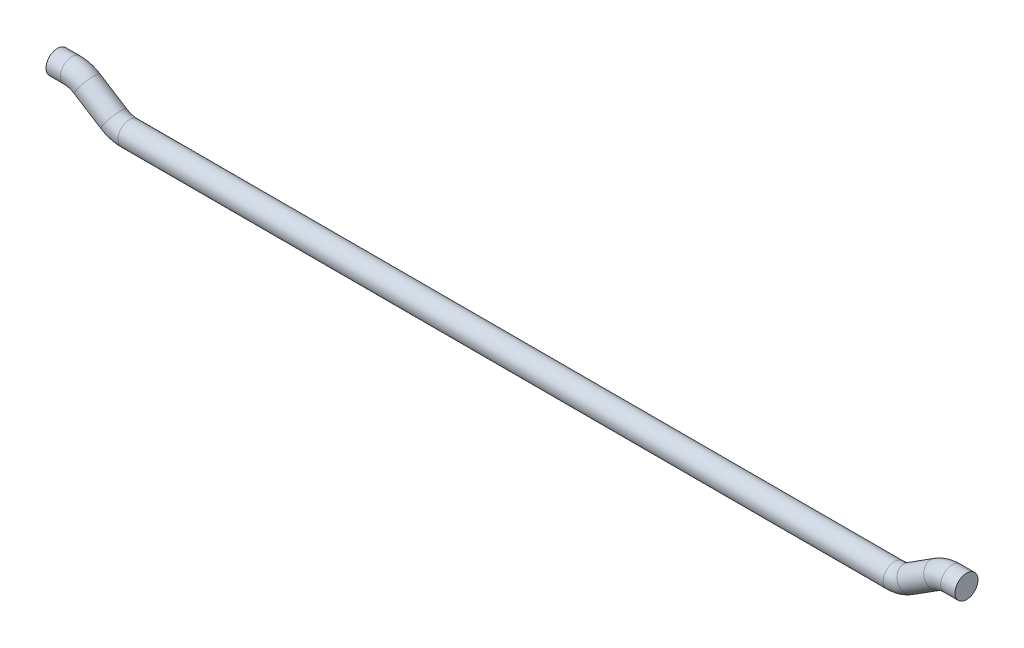
SolidWorks part; units mm, degrees
ref_plane "Front Plane" through (0, 0, 0) normal (0, 0, 1) x (1, 0, 0)
ref_plane "Top Plane" through (0, 0, 0) normal (0, 1, 0) x (1, 0, 0)
ref_plane "Right Plane" through (0, 0, 0) normal (1, 0, 0) x (0, 0, -1)
sketch "Sketch1" plane through (0, 0, 0) normal (1, 0, 0) x (0, 0, -1)
  circle A0 centre (0, 0) radius 0.8
  dimension "D1" = 1.6
sketch "Sketch2" plane through (0, 0, 0) normal (0, 0, 1) x (1, 0, 0)
  line L0 (0, 0) -> (1, 0)
  line L1 (2.071, -0.3109) -> (3.929, -1.4891)
  line L2 (5, -1.8) -> (58.25, -1.8)
  line L3 (59.321, -1.4891) -> (61.179, -0.3109)
  line L4 (62.25, 0) -> (63.25, 0)
  arc A0 (62.25, 0) -> (61.179, -0.3109) centre (62.25, -2) ccw
  arc A1 (3.929, -1.4891) -> (5, -1.8) centre (5, 0.2) ccw
  arc A2 (1, 0) -> (2.071, -0.3109) centre (1, -2) cw
  arc A3 (59.321, -1.4891) -> (58.25, -1.8) centre (58.25, 0.2) cw
  point P8 (61.6694, 0)
  dimension "D1" = 1.8
  dimension "D5" = 2
  dimension "D7" = 2
  dimension "D8" = 4
  dimension "D2" = 63.25
  dimension "D3" = 1
  dimension "D4" = 1
  dimension "D6" = 1.8
  dimension "D9" = 4
sweep "Sweep1" add profiles "Sketch1" path "Sketch2"
